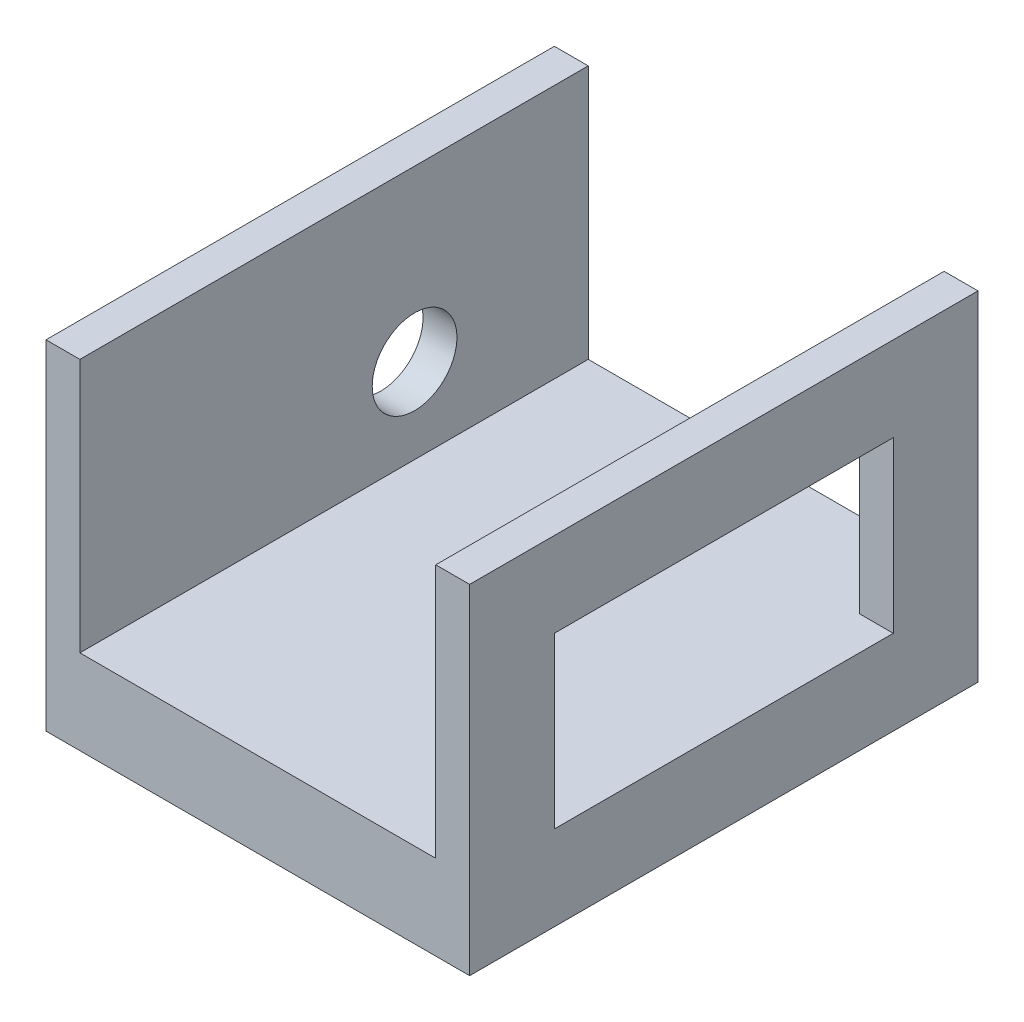
SolidWorks part; units mm, degrees
ref_plane "Front Plane" through (0, 0, 0) normal (0, 0, 1) x (1, 0, 0)
ref_plane "Top Plane" through (0, 0, 0) normal (0, 1, 0) x (1, 0, 0)
ref_plane "Right Plane" through (0, 0, 0) normal (1, 0, 0) x (0, 0, -1)
sketch "Sketch4" plane through (0, 0, 0) normal (0, 1, 0) x (1, 0, 0)
  line L1 (-25, 30) -> (25, 30)
  line L2 (-25, 30) -> (-25, -30)
  line L3 (-25, -30) -> (25, -30)
  line L4 (25, 30) -> (25, -30)
  line L5 (-25, 30) -> (25, -30) construction
  line L6 (-25, -30) -> (25, 30) construction
  point P0 (0, 0)
  dimension "D1" = 60
  dimension "D2" = 50
extrude "Boss-Extrude6" add sketch "Sketch4" along normal blind 40
sketch "Sketch9" plane through (0, 0, 30) normal (0, 0, 1) x (1, 0, 0)
  line L0 (25, 40) -> (25, 0) construction
  line L1 (-21, 10) -> (21, 10)
  line L2 (-21, 10) -> (-21, 66.4208)
  line L3 (-21, 66.4208) -> (21, 66.4208)
  line L4 (21, 10) -> (21, 66.4208)
  line L5 (-25, 40) -> (-25, 0) construction
  line L6 (-25, 0) -> (25, 0) construction
  dimension "D1" = 4
  dimension "D2" = 4
  dimension "D3" = 10
extrude "Cut-Extrude3" cut sketch "Sketch9" against normal blind 60
sketch "Sketch10" plane through (25, 0, 0) normal (1, 0, 0) x (0, 0, -1)
  line L0 (-30, 0) -> (30, 0) construction
  line L1 (-20, 10) -> (20, 10)
  line L2 (-20, 10) -> (-20, 30)
  line L3 (-20, 30) -> (20, 30)
  line L4 (20, 10) -> (20, 30)
  point P4 (0, 10)
  dimension "D1" = 40
  dimension "D2" = 20
  dimension "D3" = 10
extrude "Cut-Extrude4" cut sketch "Sketch10" against normal blind 20
sketch "Sketch11" plane through (-25, 0, 0) normal (-1, 0, 0) x (0, 0, 1)
  line L0 (-30, 40) -> (-30, 0) construction
  circle A0 centre (-9.5, 20) radius 5
  dimension "D1" = 20.5
  dimension "D3" = 10
  dimension "D2" = 10
extrude "Cut-Extrude5" cut sketch "Sketch11" against normal blind 10
